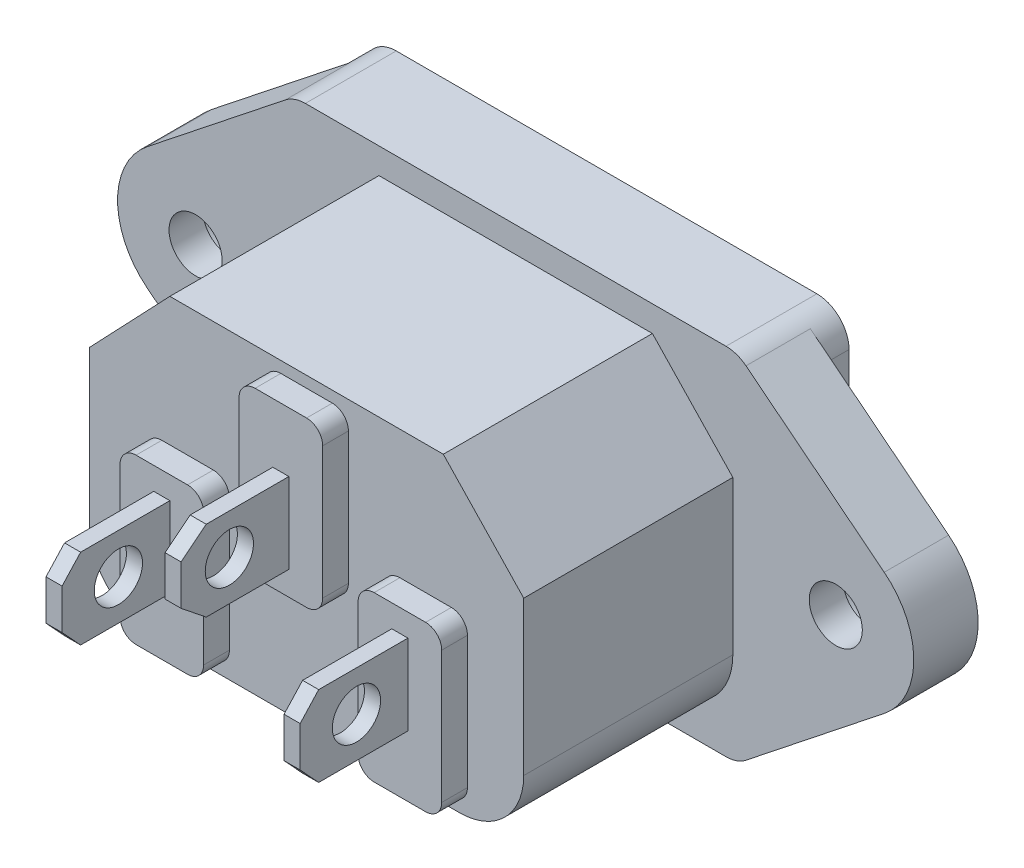
SolidWorks part; units mm, degrees
ref_plane "Front Plane" through (0, 0, 0) normal (0, 0, 1) x (1, 0, 0)
ref_plane "Top Plane" through (0, 0, 0) normal (0, 1, 0) x (1, 0, 0)
ref_plane "Right Plane" through (0, 0, 0) normal (1, 0, 0) x (0, 0, -1)
sketch "Sketch1" plane through (0, 0, 0) normal (0, 0, 1) x (1, 0, 0)
  line L1 (-13.075, -11.05) -> (13.075, -11.05)
  line L2 (-15.075, -9.05) -> (-15.075, 9.05)
  line L3 (-13.075, 11.05) -> (13.075, 11.05)
  line L4 (15.075, -9.05) -> (15.075, 9.05)
  line L5 (-15.075, -11.05) -> (15.075, 11.05) construction
  line L6 (-15.075, 11.05) -> (15.075, -11.05) construction
  arc A0 (13.075, -11.05) -> (15.075, -9.05) centre (13.075, -9.05) ccw
  arc A1 (-13.075, -11.05) -> (-15.075, -9.05) centre (-13.075, -9.05) cw
  arc A2 (-15.075, 9.05) -> (-13.075, 11.05) centre (-13.075, 9.05) cw
  arc A3 (13.075, 11.05) -> (15.075, 9.05) centre (13.075, 9.05) cw
  point P0 (0, 0)
  dimension "D3" = 2
  dimension "D1" = 22.1
  dimension "D2" = 30.15
extrude "Boss-Extrude1" add sketch "Sketch1" along normal blind 1.65
sketch "Sketch2" plane through (0, 0, 1.65) normal (0, 0, 1) x (1, 0, 0)
  line L0 (14.3177, 10.617) -> (22.9136, 3.8001)
  line L1 (22.9136, -3.8001) -> (14.3177, -10.617)
  line L2 (13.075, -11.05) -> (-13.075, -11.05)
  line L3 (-14.3177, -10.617) -> (-22.9136, -3.8001)
  line L4 (-22.9136, 3.8001) -> (-14.3177, 10.617)
  line L5 (-13.075, 11.05) -> (13.075, 11.05)
  line L6 (13.075, 11.05) -> (-13.075, 11.05) construction
  line L7 (-13.075, -11.05) -> (13.075, -11.05) construction
  arc A0 (22.9136, 3.8001) -> (22.9136, -3.8001) centre (19.9, 0) cw
  arc A1 (-22.9136, -3.8001) -> (-22.9136, 3.8001) centre (-19.9, 0) cw
  circle A2 centre (19.9, 0) radius 1.65
  circle A3 centre (-19.9, 0) radius 1.65
  arc A4 (14.3177, -10.617) -> (13.075, -11.05) centre (13.075, -9.05) cw
  arc A5 (-13.075, -11.05) -> (-14.3177, -10.617) centre (-13.075, -9.05) cw
  arc A6 (14.3177, 10.617) -> (13.075, 11.05) centre (13.075, 9.05) ccw
  arc A7 (-14.3177, 10.617) -> (-13.075, 11.05) centre (-13.075, 9.05) cw
  point P23 (24.75, 0)
  point P24 (-24.75, 0)
  dimension "D2" = 3.3
  dimension "D3" = 39.8
  dimension "D4" = 2
  dimension "D1" = 49.5
extrude "Boss-Extrude2" add sketch "Sketch2" along normal blind 4
sketch "Sketch3" plane through (0, 0, 5.65) normal (0, 0, 1) x (1, 0, 0)
  line L0 (-8.5, 9.45) -> (8.5, 9.45)
  line L1 (8.5, 9.45) -> (13.5, 4.2)
  line L2 (13.5, 4.2) -> (13.5, -9.35)
  line L3 (13.5, -9.35) -> (-13.5, -9.35)
  line L4 (-13.5, -9.35) -> (-13.5, 4.2)
  line L5 (-13.5, 4.2) -> (-8.5, 9.45)
  line L6 (-13.075, -11.05) -> (13.075, -11.05) construction
  point P2 (0, 9.45)
  point P7 (0, -9.35)
  dimension "D1" = 18.8
  dimension "D2" = 1.7
  dimension "D3" = 27
  dimension "D4" = 17
  dimension "D5" = 13.55
extrude "Boss-Extrude3" add sketch "Sketch3" along normal blind 13
sketch "Sketch4" plane through (0, 0, 0) normal (0, 0, -1) x (-1, 0, 0)
  line L0 (-8.35, 7.95) -> (8.35, 7.95)
  line L1 (8.35, 7.95) -> (12, 4.55)
  line L2 (12, 4.55) -> (12, -7.65)
  line L3 (12, -7.65) -> (-12, -7.65)
  line L4 (-12, -7.65) -> (-12, 4.55)
  line L5 (-12, 4.55) -> (-8.35, 7.95)
  line L6 (-13.075, 11.05) -> (13.075, 11.05) construction
  point P2 (0, 7.95)
  point P7 (0, -7.65)
  dimension "D1" = 15.6
  dimension "D2" = 24
  dimension "D3" = 12.2
  dimension "D4" = 16.7
  dimension "D5" = 3.1
extrude "Cut-Extrude1" cut sketch "Sketch4" against normal blind 16.5
fillet "Fillet1" radius 4 2 edges at (-13.5, -9.35, 12.15) (13.5, -9.35, 12.15)
fillet "Fillet2" radius 3 2 edges at (-12, -7.65, 8.25) (12, -7.65, 8.25)
sketch "Sketch5" plane through (0, 0, 1.65) normal (0, 0, -1) x (-1, 0, 0)
  circle A0 centre (-19.9, 0) radius 2.5
  circle A1 centre (19.9, 0) radius 2.5
  dimension "D1" = 5
extrude "Cut-Extrude2" cut sketch "Sketch5" against normal blind 1.9
sketch "Sketch6" plane through (0, 0, 18.65) normal (0, 0, 1) x (1, 0, 0)
  line L0 (13.5, -5.35) -> (13.5, 4.2) construction
  line L1 (-2.6, 8.75) -> (2.6, 8.75)
  line L2 (-2.6, 8.75) -> (-2.6, -1.45)
  line L3 (-2.6, -1.45) -> (2.6, -1.45)
  line L4 (2.6, 8.75) -> (2.6, -1.45)
  line L5 (4.8, 1.45) -> (10, 1.45)
  line L6 (4.8, 1.45) -> (4.8, -8.75)
  line L7 (4.8, -8.75) -> (10, -8.75)
  line L8 (10, 1.45) -> (10, -8.75)
  line L9 (-10, 1.45) -> (-4.8, 1.45)
  line L10 (-10, 1.45) -> (-10, -8.75)
  line L11 (-10, -8.75) -> (-4.8, -8.75)
  line L12 (-4.8, 1.45) -> (-4.8, -8.75)
  line L13 (-13.5, 4.2) -> (-13.5, -5.35) construction
  line L14 (-9.5, -9.35) -> (9.5, -9.35) construction
  line L15 (8.5, 9.45) -> (-8.5, 9.45) construction
  point P12 (0, -1.45)
  dimension "D1" = 5.2
  dimension "D2" = 10.2
  dimension "D3" = 8.7
  dimension "D4" = 8.7
  dimension "D5" = 0.6
  dimension "D6" = 0.7
extrude "Boss-Extrude4" add sketch "Sketch6" along normal blind 1.6
fillet "Fillet3" radius 1 12 edges at (-4.8, 1.45, 19.45) (10, 1.45, 19.45) (10, -8.75, 19.45) (4.8, -8.75, 19.45) (-10, -8.75, 19.45) (-4.8, -8.75, 19.45) (-2.6, -1.45, 19.45) (2.6, -1.45, 19.45) (2.6, 8.75, 19.45) (4.8, 1.45, 19.45) (-2.6, 8.75, 19.45) (-10, 1.45, 19.45)
sketch "Sketch7" plane through (0, 0, 16.5) normal (0, 0, -1) x (-1, 0, 0)
  line L0 (-10, -7.75) -> (-10, 0.45) construction
  line L1 (-9, 1.45) -> (-5.8, 1.45) construction
  line L2 (-4.8, 0.45) -> (-4.8, -7.75) construction
  line L3 (-5.8, -8.75) -> (-9, -8.75) construction
  line L4 (2.6, 7.75) -> (2.6, -0.45) construction
  line L5 (1.6, -1.45) -> (-1.6, -1.45) construction
  line L6 (-2.6, -0.45) -> (-2.6, 7.75) construction
  line L7 (-1.6, 8.75) -> (1.6, 8.75) construction
  line L8 (10, 0.45) -> (10, -7.75) construction
  line L9 (9, -8.75) -> (5.8, -8.75) construction
  line L10 (4.8, -7.75) -> (4.8, 0.45) construction
  line L11 (5.8, 1.45) -> (9, 1.45) construction
  line L12 (-10, -7.75) -> (-10, 0.45) construction
  line L13 (-9, 1.45) -> (-5.8, 1.45) construction
  line L14 (-4.8, 0.45) -> (-4.8, -7.75) construction
  line L15 (-5.8, -8.75) -> (-9, -8.75) construction
  line L16 (2.6, 7.75) -> (2.6, -0.45) construction
  line L17 (1.6, -1.45) -> (-1.6, -1.45) construction
  line L18 (-2.6, -0.45) -> (-2.6, 7.75) construction
  line L19 (-1.6, 8.75) -> (1.6, 8.75) construction
  line L20 (10, 0.45) -> (10, -7.75) construction
  line L21 (9, -8.75) -> (5.8, -8.75) construction
  line L22 (4.8, -7.75) -> (4.8, 0.45) construction
  line L23 (5.8, 1.45) -> (9, 1.45) construction
  line L24 (13.075, -11.05) -> (-13.075, -11.05) construction
  line L25 (-1.05, 4.05) -> (1.05, 4.05)
  line L26 (-1.05, 4.05) -> (-1.05, 0.05)
  line L27 (-1.05, 0.05) -> (1.05, 0.05)
  line L28 (1.05, 4.05) -> (1.05, 0.05)
  line L29 (-8.45, -0.05) -> (-6.35, -0.05)
  line L30 (-8.45, -0.05) -> (-8.45, -4.05)
  line L31 (-8.45, -4.05) -> (-6.35, -4.05)
  line L32 (-6.35, -0.05) -> (-6.35, -4.05)
  line L33 (6.35, -0.05) -> (8.45, -0.05)
  line L34 (6.35, -0.05) -> (6.35, -4.05)
  line L35 (6.35, -4.05) -> (8.45, -4.05)
  line L36 (8.45, -0.05) -> (8.45, -4.05)
  line L37 (-13.075, 11.05) -> (13.075, 11.05) construction
  arc A0 (-9, 1.45) -> (-10, 0.45) centre (-9, 0.45) ccw construction
  arc A1 (-4.8, 0.45) -> (-5.8, 1.45) centre (-5.8, 0.45) ccw construction
  arc A2 (-5.8, -8.75) -> (-4.8, -7.75) centre (-5.8, -7.75) ccw construction
  arc A3 (-10, -7.75) -> (-9, -8.75) centre (-9, -7.75) ccw construction
  arc A4 (1.6, -1.45) -> (2.6, -0.45) centre (1.6, -0.45) ccw construction
  arc A5 (-2.6, -0.45) -> (-1.6, -1.45) centre (-1.6, -0.45) ccw construction
  arc A6 (-1.6, 8.75) -> (-2.6, 7.75) centre (-1.6, 7.75) ccw construction
  arc A7 (2.6, 7.75) -> (1.6, 8.75) centre (1.6, 7.75) ccw construction
  arc A8 (9, -8.75) -> (10, -7.75) centre (9, -7.75) ccw construction
  arc A9 (4.8, -7.75) -> (5.8, -8.75) centre (5.8, -7.75) ccw construction
  arc A10 (5.8, 1.45) -> (4.8, 0.45) centre (5.8, 0.45) ccw construction
  arc A11 (10, 0.45) -> (9, 1.45) centre (9, 0.45) ccw construction
  arc A12 (-9, 1.45) -> (-10, 0.45) centre (-9, 0.45) ccw construction
  arc A13 (-4.8, 0.45) -> (-5.8, 1.45) centre (-5.8, 0.45) ccw construction
  arc A14 (-5.8, -8.75) -> (-4.8, -7.75) centre (-5.8, -7.75) ccw construction
  arc A15 (-10, -7.75) -> (-9, -8.75) centre (-9, -7.75) ccw construction
  arc A16 (1.6, -1.45) -> (2.6, -0.45) centre (1.6, -0.45) ccw construction
  arc A17 (-2.6, -0.45) -> (-1.6, -1.45) centre (-1.6, -0.45) ccw construction
  arc A18 (-1.6, 8.75) -> (-2.6, 7.75) centre (-1.6, 7.75) ccw construction
  arc A19 (2.6, 7.75) -> (1.6, 8.75) centre (1.6, 7.75) ccw construction
  arc A20 (9, -8.75) -> (10, -7.75) centre (9, -7.75) ccw construction
  arc A21 (4.8, -7.75) -> (5.8, -8.75) centre (5.8, -7.75) ccw construction
  arc A22 (5.8, 1.45) -> (4.8, 0.45) centre (5.8, 0.45) ccw construction
  arc A23 (10, 0.45) -> (9, 1.45) centre (9, 0.45) ccw construction
  point P14 (0, 0.05)
  point P35 (-7.4, -0.05)
  point P38 (-7.4, 1.45)
  point P39 (7.4, -0.05)
  point P44 (7.4, 1.45)
  dimension "D1" = 2.1
  dimension "D2" = 4
  dimension "D3" = 11
  dimension "D4" = 11
extrude "Boss-Extrude5" add sketch "Sketch7" along normal blind 15.2
fillet "Fillet4" radius 1 6 edges at (-6.35, -2.05, 1.3) (-8.45, -2.05, 1.3) (1.05, 2.05, 1.3) (-1.05, 2.05, 1.3) (8.45, -2.05, 1.3) (6.35, -2.05, 1.3)
sketch "Sketch8" plane through (0, 0, 20.25) normal (0, 0, 1) x (1, 0, 0)
  line L0 (-9, -8.75) -> (-5.8, -8.75) construction
  line L1 (-7.9, 0.05) -> (-6.9, 0.05)
  line L2 (-7.9, 0.05) -> (-7.9, -4.95)
  line L3 (-7.9, -4.95) -> (-6.9, -4.95)
  line L4 (-6.9, 0.05) -> (-6.9, -4.95)
  line L5 (-0.5, 0.05) -> (0.5, 0.05)
  line L6 (-0.5, 0.05) -> (-0.5, 5.05)
  line L7 (-0.5, 5.05) -> (0.5, 5.05)
  line L8 (0.5, 0.05) -> (0.5, 5.05)
  line L9 (6.9, 0.05) -> (7.9, 0.05)
  line L10 (6.9, 0.05) -> (6.9, -4.95)
  line L11 (6.9, -4.95) -> (7.9, -4.95)
  line L12 (7.9, 0.05) -> (7.9, -4.95)
  line L13 (-1.6, -1.45) -> (1.6, -1.45) construction
  line L14 (5.8, -8.75) -> (9, -8.75) construction
  point P12 (-7.4, -4.95)
  point P15 (-7.4, -8.75)
  point P16 (0, 0.05)
  point P19 (0, -1.45)
  point P20 (7.4, -4.95)
  point P23 (7.4, -8.75)
  dimension "D1" = 5
  dimension "D2" = 1
  dimension "D3" = 8.8
extrude "Boss-Extrude6" add sketch "Sketch8" along normal blind 6.7
sketch "Sketch9" plane through (-7.9, 0, 0) normal (-1, 0, 0) x (0, 0, 1)
  line L0 (25.7978, 0.05) -> (26.95, -1.2)
  line L1 (26.95, 0.05) -> (20.25, 0.05) construction
  line L2 (26.95, 0.05) -> (26.95, -4.95) construction
  line L3 (26.95, -1.2) -> (26.95, 0.05)
  line L4 (26.95, 0.05) -> (25.7978, 0.05)
  line L5 (26.95, -3.7) -> (25.7978, -4.95)
  line L6 (26.95, -4.95) -> (20.25, -4.95) construction
  line L7 (25.7978, -4.95) -> (26.95, -4.95)
  line L8 (26.95, -4.95) -> (26.95, -3.7)
  circle A0 centre (23.45, -2.45) radius 1.5
  point P18 (26.95, -2.45)
  dimension "D3" = 3
  dimension "D1" = 2.5
  dimension "D2" = 1.7
  dimension "D4" = 3.5
extrude "Cut-Extrude3" cut sketch "Sketch9" against normal through all
sketch "Sketch10" plane through (-0.5, 0, 0) normal (-1, 0, 0) x (0, 0, 1)
  line L0 (25.3888, 5.05) -> (26.95, 3.8)
  line L1 (26.95, 3.8) -> (26.95, 5.05)
  line L2 (26.95, 5.05) -> (25.3888, 5.05)
  line L3 (26.95, 1.3) -> (25.3888, 0.05)
  line L4 (25.3888, 0.05) -> (26.95, 0.05)
  line L5 (26.95, 0.05) -> (26.95, 1.3)
  line L6 (26.95, 5.05) -> (26.95, 0.05) construction
  line L7 (26.95, 5.05) -> (20.25, 5.05) construction
  line L8 (26.95, 0.05) -> (20.25, 0.05) construction
  line L9 (26.95, 0.05) -> (26.95, 5.05) construction
  circle A0 centre (23.95, 2.55) radius 1.5
  point P15 (26.95, 2.55)
  dimension "D3" = 3
  dimension "D4" = 3
  dimension "D1" = 2
  dimension "D2" = 2.5
extrude "Cut-Extrude4" cut sketch "Sketch10" against normal up to next
